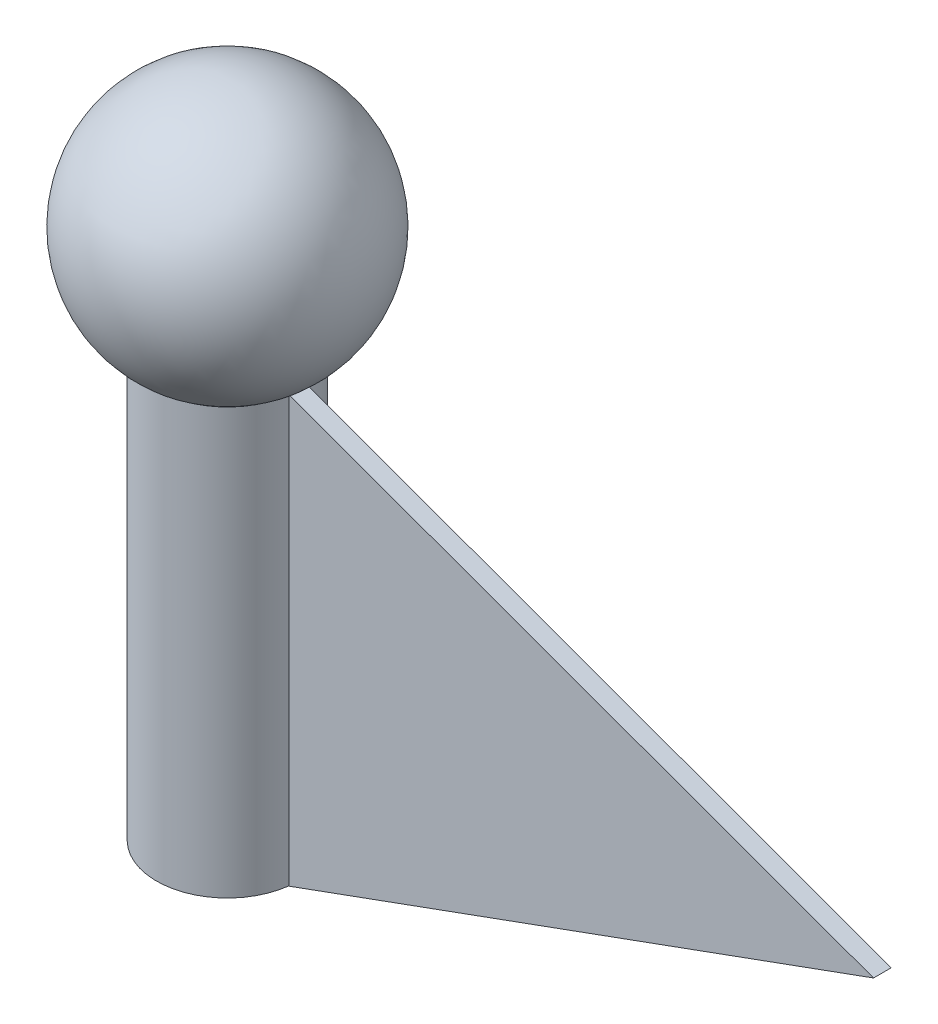
SolidWorks part; units mm, degrees
ref_plane "Front Plane" through (0, 0, 0) normal (0, 0, 1) x (1, 0, 0)
ref_plane "Top Plane" through (0, 0, 0) normal (0, 1, 0) x (1, 0, 0)
ref_plane "Right Plane" through (0, 0, 0) normal (1, 0, 0) x (0, 0, -1)
sketch "Sketch2" plane through (0, 0, 0) normal (0, 1, 0) x (1, 0, 0)
  circle A0 centre (0, 0) radius 25.4
  dimension "D1" = 50.8
extrude "Boss-Extrude1" add sketch "Sketch2" along normal blind 152.4
hole_wizard "1 NPT Tapped Hole1" positions "Sketch4" profile "Sketch5" size "1" standard "ANSI Inch"
sketch "Sketch4" plane through (0, 0, 0) normal (0, -1, 0) x (1, 0, 0)
  point P0 (0, 0)
cosmetic thread "Hole Thread2" parameters "D1"=16.764, "D2"=33.3986
sketch "Sketch5" plane through (0, 0, 0) normal (1, 0, 0) x (0, 0, -1)
  line L0 (0, 0) -> (0, 59.5069)
  line L1 (14.4907, 50.8) -> (0, 59.5069)
  line L2 (-14.4907, 50.8) -> (0, 59.5069) construction
  line L3 (14.4907, 50.8) -> (14.4907, 16.764)
  line L4 (14.4907, 16.764) -> (15.2065, 16.764)
  line L5 (15.2065, 16.764) -> (15.7299, 0)
  line L6 (-15.2065, 16.764) -> (-15.7299, 0) construction
  line L7 (15.7299, 0) -> (0, 0)
  line L8 (0, -6.35) -> (0, 107.95) construction
  line L11 (-14.4907, 16.764) -> (-15.2065, 16.764) construction
  dimension "Tap Drill Dia." = 28.9814
  dimension "Tap Drill Depth" = 50.8
  dimension "Thread Dia." = 31.4598
  dimension "Thread Angle" = 3.576
  dimension "Thread Depth" = 16.764
  dimension "Drill Angle" = 118
sketch "Sketch7" plane through (0, 0, 0) normal (0, 0, 1) x (1, 0, 0)
  line L0 (25.4, 152.4) -> (234.7578, 76.2)
  line L1 (25.4, 0) -> (234.7578, 76.2)
  line L2 (25.4, 0) -> (25.4, 152.4) construction
  line L3 (-25.4, 0) -> (25.4, 0) construction
  line L5 (25.4, 152.4) -> (20.4927, 152.4)
  line L6 (25.4, 152.4) -> (-25.4, 152.4) construction
  line L7 (20.4927, 152.4) -> (20.4927, 0)
  line L8 (20.4927, 0) -> (25.4, 0)
  dimension "D1" = 70
  dimension "D2" = 76.2
  dimension "D3" = 70
extrude "Boss-Extrude2" add sketch "Sketch7" along normal mid plane 6.35 separate body contours L0 L1 L8 L7 L5
sketch "Sketch8" plane through (0, 0, 0) normal (0, 0, 1) x (1, 0, 0)
  line L1 (25.4, 152.4) -> (0, 152.4)
  line L2 (0, 152.4) -> (0, 236.2905)
  arc A1 (25.4, 152.4) -> (0, 236.2905) centre (0, 190.5) ccw
revolve "Revolve1" add sketch "Sketch8" angle 360 about L2
